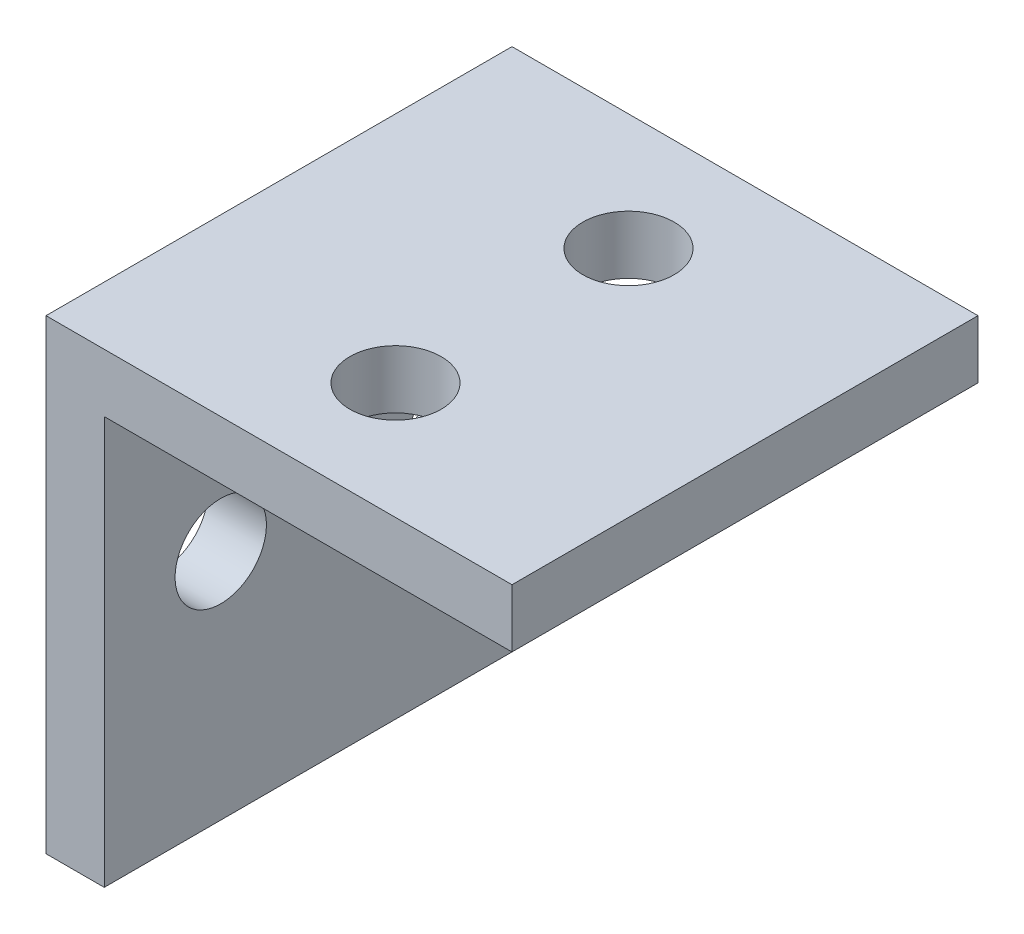
SolidWorks part; units mm, degrees
ref_plane "Front Plane" through (0, 0, 0) normal (0, 0, 1) x (1, 0, 0)
ref_plane "Top Plane" through (0, 0, 0) normal (0, 1, 0) x (1, 0, 0)
ref_plane "Right Plane" through (0, 0, 0) normal (1, 0, 0) x (0, 0, -1)
sketch "Sketch2" plane through (0, 0, 0) normal (0, 0, 1) x (1, 0, 0)
  line L0 (0, 0) -> (0, -25.4)
  line L1 (0, -25.4) -> (3.175, -25.4)
  line L2 (3.175, -25.4) -> (3.175, -3.175)
  line L3 (3.175, -3.175) -> (25.4, -3.175)
  line L4 (25.4, -3.175) -> (25.4, 0)
  line L5 (25.4, 0) -> (0, 0)
  dimension "D1" = 3.175
  dimension "D2" = 25.4
  dimension "D3" = 25.4
extrude "Boss-Extrude1" add sketch "Sketch2" along normal blind 25.4
sketch "Sketch5" plane through (3.175, 0, 0) normal (1, 0, 0) x (0, 0, -1)
  line L0 (-25.4, -25.4) -> (0, -25.4) construction
  line L1 (0, -25.4) -> (0, -3.175) construction
  circle A1 centre (-6.35, -12.7) radius 2.4892
  circle A2 centre (-19.05, -12.7) radius 2.4892
  circle A3 centre (-31.75, -12.7) radius 2.4892
  circle A4 centre (-44.45, -12.7) radius 2.4892
  dimension "D1" = 4.9784
  dimension "D2" = 12.7
  dimension "D3" = 6.35
  dimension "D4" = 4
  dimension "D5" = 12.7
extrude "Cut-Extrude1" cut sketch "Sketch5" against normal through all
sketch "Sketch6" plane through (0, -3.175, 0) normal (0, -1, 0) x (1, 0, 0)
  line L0 (3.175, 0) -> (25.4, 0) construction
  line L1 (25.4, 25.4) -> (25.4, 0) construction
  circle A0 centre (12.7, 6.35) radius 2.4892
  circle A1 centre (12.7, 19.05) radius 2.4892
  circle A2 centre (12.7, 31.75) radius 2.4892
  circle A3 centre (12.7, 44.45) radius 2.4892
  dimension "D3" = 4.9784
  dimension "D1" = 6.35
  dimension "D2" = 12.7
  dimension "D5" = 12.7
  dimension "D4" = 4
extrude "Cut-Extrude2" cut sketch "Sketch6" against normal through all
